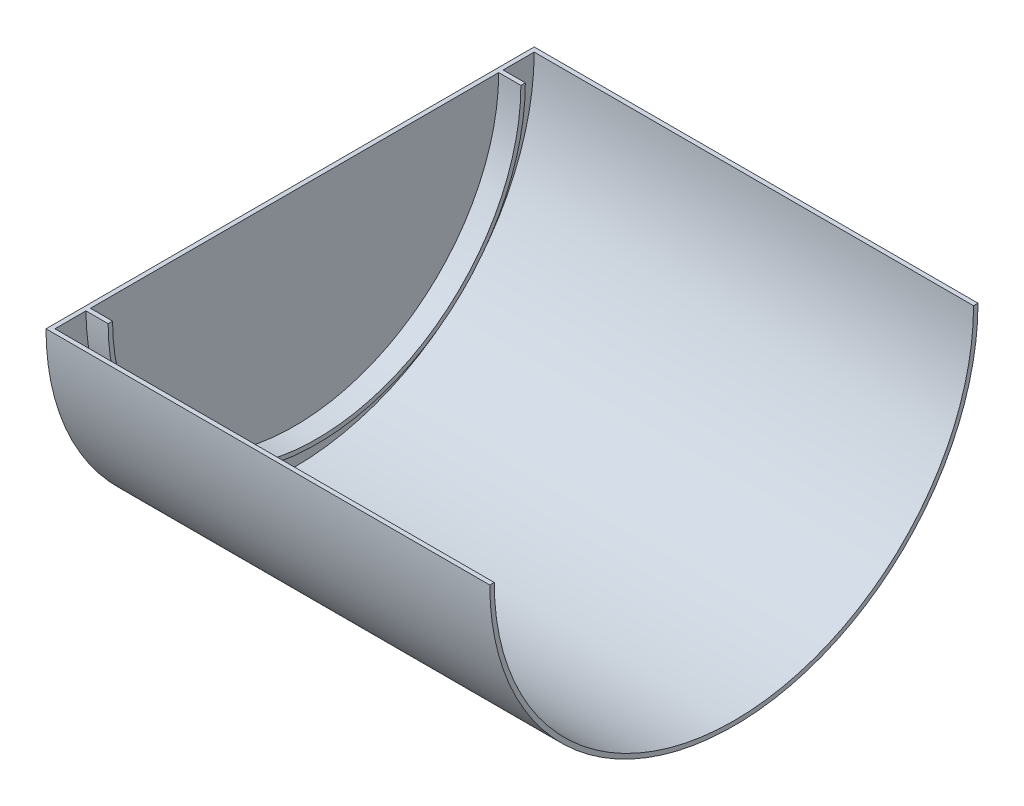
SolidWorks part; units mm, degrees
ref_plane "Front Plane" through (0, 0, 0) normal (0, 0, 1) x (1, 0, 0)
ref_plane "Top Plane" through (0, 0, 0) normal (0, 1, 0) x (1, 0, 0)
ref_plane "Right Plane" through (0, 0, 0) normal (1, 0, 0) x (0, 0, -1)
sketch "Sketch1" plane through (0, 0, 0) normal (1, 0, 0) x (0, 0, -1)
  line L0 (-55, 0) -> (55, 0)
  arc A0 (55, 0) -> (-55, 0) centre (0, 0) cw
extrude "Boss-Extrude2" add sketch "Sketch1" along normal blind 100 contours A0 L0
sketch "Sketch5" plane through (100, 0, 0) normal (1, 0, 0) x (0, 0, -1)
  line L0 (-55, 0) -> (55, 0) construction
  line L1 (-54, 0) -> (54, 0)
  arc A0 (-54, 0) -> (54, 0) centre (0, 0) ccw
extrude "Cut-Extrude1" cut sketch "Sketch5" against normal blind 99
sketch "Sketch6" plane through (1, 0, 0) normal (1, 0, 0) x (0, 0, -1)
  line L0 (54, 0) -> (-54, 0) construction
  arc A0 (47, 0) -> (-47, 0) centre (0, 0) cw
extrude "Extrude-Thin1" add sketch "Sketch6" along normal blind 5 thin
